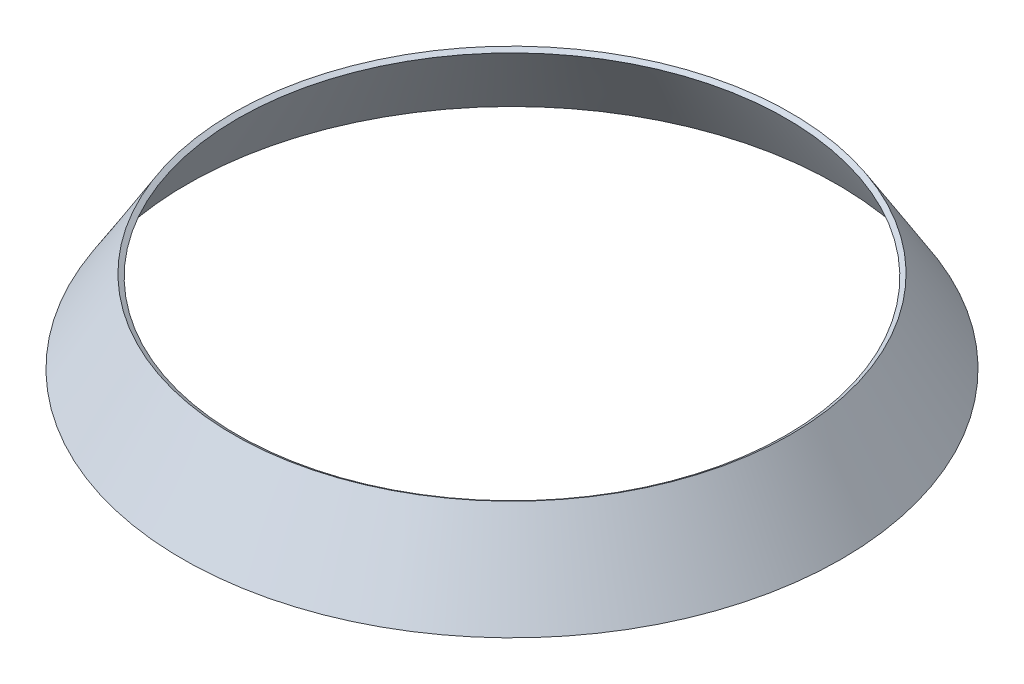
SolidWorks part; units mm, degrees
ref_plane "Front Plane" through (0, 0, 0) normal (0, 0, 1) x (1, 0, 0)
ref_plane "Top Plane" through (0, 0, 0) normal (0, 1, 0) x (1, 0, 0)
ref_plane "Right Plane" through (0, 0, 0) normal (1, 0, 0) x (0, 0, -1)
sketch "Sketch1" plane through (0, 0, 0) normal (0, 0, 1) x (1, 0, 0)
  line L0 (0, -1106.9178) -> (0, 54238.9737) construction
  line L1 (37.4234, 5.7142) -> (44.2545, -5.3464)
  line L2 (37.4234, 5.7142) -> (36.8278, 5.3464)
  line L3 (44.2545, -5.3464) -> (43.659, -5.7142)
  line L4 (36.8278, 5.3464) -> (43.659, -5.7142)
  line L5 (37.4234, 5.7142) -> (43.659, -5.7142) construction
  line L6 (44.2545, -5.3464) -> (36.8278, 5.3464) construction
  point P4 (40.5412, 0)
  dimension "D1" = 31.7
  dimension "D2" = 0.7
  dimension "D4" = 13
  dimension "D5" = 37.4234
revolve "Revolve1" add sketch "Sketch1" angle 360 about L0
